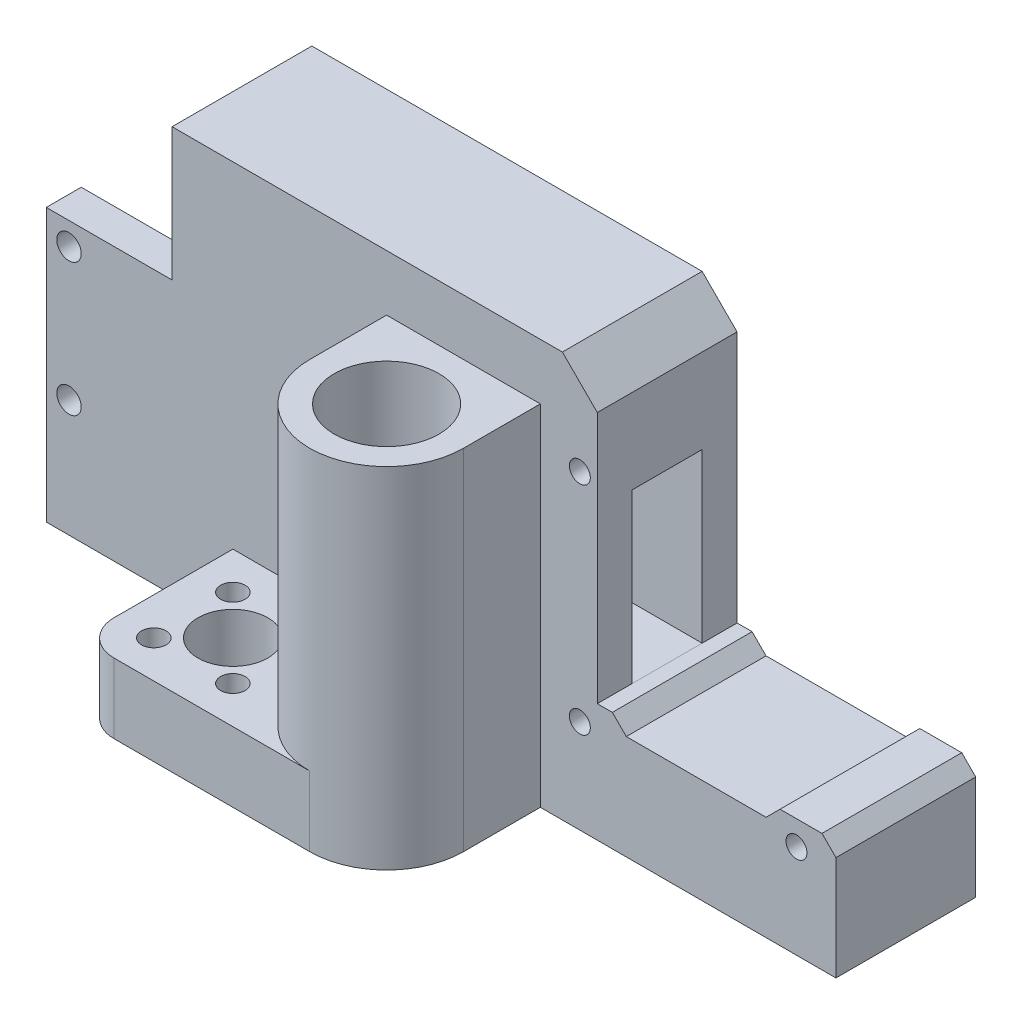
SolidWorks part; units mm, degrees
ref_plane "前视基准面" through (0, 0, 0) normal (0, 0, 1) x (1, 0, 0)
ref_plane "上视基准面" through (0, 0, 0) normal (0, 1, 0) x (1, 0, 0)
ref_plane "右视基准面" through (0, 0, 0) normal (1, 0, 0) x (0, 0, -1)
sketch "草图1" plane through (0, 0, 0) normal (0, 0, 1) x (1, 0, 0)
  line L0 (-18, 29.0798) -> (-13, 24.0798)
  line L1 (-13, 24.0798) -> (-13.0003, -12.0002)
  line L2 (19.15, -12.0002) -> (21.15, -14.0002)
  line L3 (-10.85, -12.0002) -> (-8.85, -14.0002)
  line L4 (21.15, -14.0002) -> (21.15, -28.9202)
  line L5 (21.15, -28.9202) -> (-73.85, -28.9202)
  line L6 (-73.85, -28.9202) -> (-73.85, 29.0798)
  line L7 (-13.0003, -12.0002) -> (-10.85, -12.0002)
  line L8 (-8.85, -14.0002) -> (11.15, -14.0002)
  line L9 (-73.85, 29.0798) -> (-18, 29.0798)
  line L11 (11.15, -14.0002) -> (13.15, -12.0002)
  line L12 (13.15, -12.0002) -> (19.15, -12.0002)
  point P2 (-13, 29.0798)
  point P12 (21.15, -12.0002)
  dimension "D1" = 20
  dimension "D2" = 95
  dimension "D3" = 58
extrude "凸台-拉伸1" add sketch "草图1" along normal blind 20
sketch "草图2" plane through (0, 0, 20) normal (0, 0, 1) x (1, 0, 0)
  circle A0 centre (-15.5, 15.5) radius 1.5 construction
  circle A1 centre (-15.5, -15.5) radius 1.5 construction
  circle A2 centre (15.5, -15.5) radius 1.5 construction
  circle A3 centre (-15.5, 15.5) radius 1.5
  circle A4 centre (-15.5, -15.5) radius 1.5
  circle A5 centre (15.5, -15.5) radius 1.5
extrude "切除-拉伸1" cut sketch "草图2" against normal blind 20
sketch "草图3" plane through (0, -28.9202, 0) normal (0, -1, 0) x (1, 0, 0)
  line L0 (-43.15, 31) -> (-43.15, 20)
  line L1 (-73.85, 20) -> (21.15, 20) construction
  line L2 (-43.15, 20) -> (-21.15, 20)
  line L3 (-21.15, 20) -> (-21.15, 31)
  line L4 (-21.15, -10) -> (-21.15, 0) construction
  arc A0 (-21.15, 31) -> (-43.15, 31) centre (-32.15, 31) ccw
  circle A1 centre (-32.15, 31) radius 7.5
  dimension "D1" = 22
  dimension "D2" = 15
  dimension "D3" = 11
extrude "凸台-拉伸2" add sketch "草图3" against normal blind 50
sketch "草图5" plane through (0, -28.9202, 0) normal (0, -1, 0) x (1, 0, 0)
  line L0 (-43.15, 42) -> (-32.15, 42)
  line L1 (-43.15, 20) -> (-65.15, 20)
  line L2 (-43.15, 31) -> (-43.15, 20) construction
  line L3 (-43.15, 42) -> (-60.15, 42)
  line L4 (-65.15, 20) -> (-65.15, 37)
  line L5 (-43.15, 31) -> (-43.15, 20)
  arc A0 (-65.15, 37) -> (-60.15, 42) centre (-60.15, 37) cw
  arc A1 (-21.15, 31) -> (-43.15, 31) centre (-32.15, 31) ccw construction
  arc A2 (-32.15, 42) -> (-43.15, 31) centre (-32.15, 31) ccw
  point P8 (-65.15, 42)
  dimension "D3" = 5
  dimension "D1" = 22
  dimension "D2" = 22
extrude "凸台-拉伸3" add sketch "草图5" against normal blind 10
sketch "草图7" plane through (0, 0, 20) normal (0, 0, 1) x (1, 0, 0)
  line L1 (-73.85, -28.9202) -> (-91.85, -28.9202)
  line L2 (-73.85, -28.9202) -> (-73.85, 10.0798)
  line L3 (-73.85, 10.0798) -> (-91.85, 10.0798)
  line L4 (-91.85, -28.9202) -> (-91.85, 10.0798)
  dimension "D1" = 18
  dimension "D2" = 39
extrude "凸台-拉伸4" add sketch "草图7" against normal blind 5
sketch "草图9" plane through (0, -28.9202, 0) normal (0, -1, 0) x (1, 0, 0)
  line L0 (-63.6855, 40.5355) -> (-42.4086, 19.2586) construction
  line L1 (-65.15, 20) -> (-44.5517, 40.5983) construction
  arc A0 (-60.15, 42) -> (-65.15, 37) centre (-60.15, 37) ccw construction
  circle A1 centre (-54.15, 31) radius 5
  circle A2 centre (-54.15, 31) radius 8 construction
  circle A3 centre (-59.8069, 36.6569) radius 1.75
  circle A4 centre (-48.4931, 36.6569) radius 1.75
  circle A5 centre (-48.4931, 25.3431) radius 1.75
  circle A6 centre (-59.8069, 25.3431) radius 1.75
  point P8 (-54.15, 31)
  point P23 (-54.15, 31)
  dimension "D1" = 10
  dimension "D2" = 16
  dimension "D3" = 3.5
  dimension "D4" = 4
extrude "切除-拉伸2" cut sketch "草图9" against normal blind 15
sketch "草图12" plane through (-73.85, 0, 0) normal (-1, 0, 0) x (0, 0, 1)
  line L0 (20, 29.0798) -> (0, 29.0798) construction
  line L1 (0, 29.0798) -> (0, -28.9202) construction
  circle A0 centre (10, 22.5798) radius 4
  circle A1 centre (10, -22.4202) radius 4
  dimension "D1" = 8
  dimension "D2" = 6.5
  dimension "D3" = 10
  dimension "D4" = 45
  dimension "D5" = 8
  dimension "D6" = 10
extrude "切除-拉伸3" cut sketch "草图12" against normal blind 20
sketch "草图13" plane through (-73.85, 0, 0) normal (-1, 0, 0) x (0, 0, 1)
  line L0 (0, 0) -> (20, 0) construction
  line L1 (20, 21.0798) -> (20, -18.9202) construction
  line L2 (10, 29.0798) -> (10, -28.9202) construction
  line L3 (20, 29.0798) -> (0, 29.0798) construction
  line L4 (15, -28.9202) -> (0, -28.9202) construction
  line L6 (5, -12) -> (15, -12)
  line L7 (5, -12) -> (5, 12)
  line L8 (5, 12) -> (15, 12)
  line L9 (15, -12) -> (15, 12)
  line L10 (5, -12) -> (15, 12) construction
  line L11 (5, 12) -> (15, -12) construction
  point P11 (10, 0)
  dimension "D1" = 10
  dimension "D2" = 24
extrude "切除-拉伸4" cut sketch "草图13" against normal up to surface (60.8497 mm away)
sketch "草图14" plane through (0, 0, 20) normal (0, 0, 1) x (1, 0, 0)
  circle A0 centre (-88.6, -12.1702) radius 1.75
  circle A1 centre (-88.6, 6.8298) radius 1.75
extrude "切除-拉伸5" cut sketch "草图14" against normal blind 10
